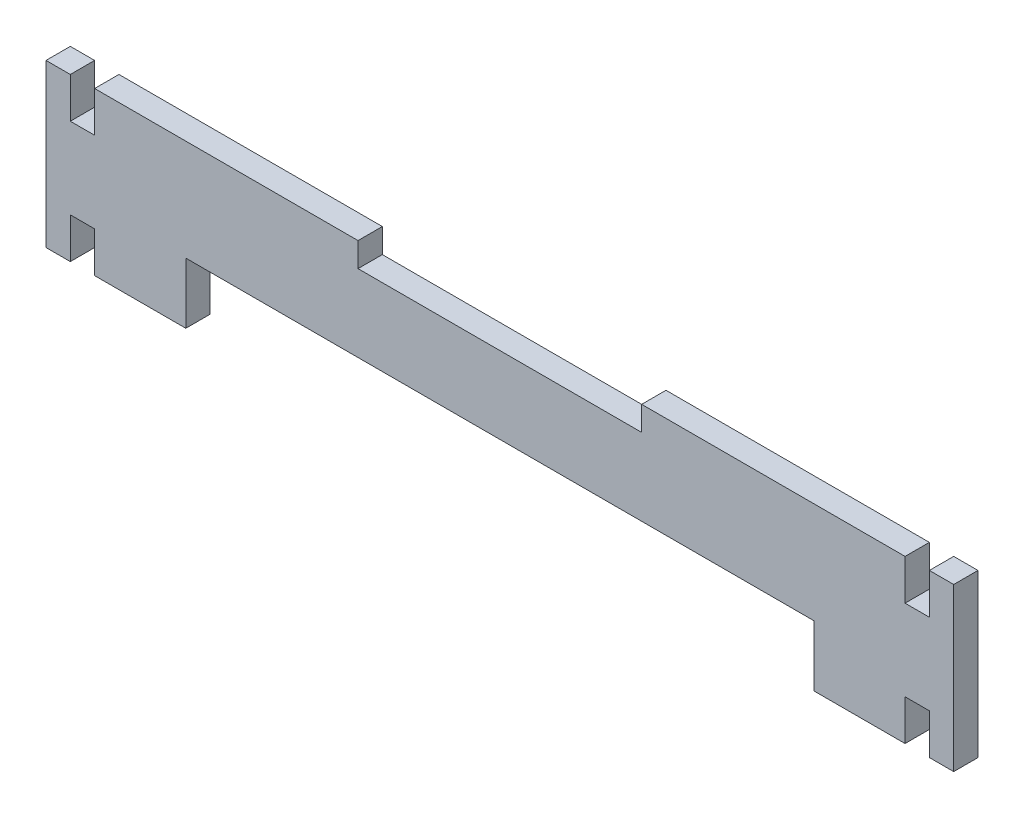
SolidWorks part; units mm, degrees
ref_plane "Front" through (0, 0, 0) normal (0, 0, 1) x (1, 0, 0)
ref_plane "Top" through (0, 0, 0) normal (0, 1, 0) x (1, 0, 0)
ref_plane "Right" through (0, 0, 0) normal (1, 0, 0) x (0, 0, -1)
sketch "Sketch1" plane through (0, 0, 0) normal (0, 0, 1) x (1, 0, 0)
  line L1 (0, 0) -> (-224, 0)
  line L2 (0, 0) -> (0, 40)
  line L3 (0, 40) -> (-224, 40)
  line L4 (-224, 0) -> (-224, 40)
  dimension "D1" = 40
  dimension "D2" = 224
extrude "Boss-Extrude1" add sketch "Sketch1" along normal blind 6
sketch "Sketch2" plane through (0, 0, 6) normal (0, 0, 1) x (1, 0, 0)
  line L0 (0, 40) -> (-224, 40) construction
  line L1 (-218, 40) -> (-212, 40)
  line L2 (-218, 40) -> (-218, 30)
  line L3 (-218, 30) -> (-212, 30)
  line L4 (-212, 40) -> (-212, 30)
  line L5 (-224, 40) -> (-224, 0) construction
  dimension "D1" = 10
  dimension "D2" = 6
  dimension "D3" = 6
extrude "Cut-Extrude1" cut sketch "Sketch2" against normal through all
pattern_linear "LPattern1" count 2 spacing 206 along (1, 0, 0) count 2 spacing 30 along (0, -1, 0) of "Cut-Extrude1"
sketch "Sketch3" plane through (0, 0, 6) normal (0, 0, 1) x (1, 0, 0)
  line L0 (-12, 40) -> (-212, 40) construction
  line L1 (-147, 40) -> (-77, 40)
  line L2 (-147, 40) -> (-147, 34)
  line L3 (-147, 34) -> (-77, 34)
  line L4 (-77, 40) -> (-77, 34)
  point P6 (-112, 40)
  point P7 (-112, 40)
  dimension "D1" = 70
  dimension "D2" = 6
extrude "Cut-Extrude2" cut sketch "Sketch3" against normal through all
sketch "Sketch4" plane through (0, 0, 6) normal (0, 0, 1) x (1, 0, 0)
  line L0 (-212, 0) -> (-12, 0) construction
  line L1 (-189.5, 0) -> (-34.5, 0)
  line L2 (-189.5, 0) -> (-189.5, 15)
  line L3 (-189.5, 15) -> (-34.5, 15)
  line L4 (-34.5, 0) -> (-34.5, 15)
  point P6 (-112, 0)
  point P7 (-112, 0)
  dimension "D1" = 15
  dimension "D2" = 155
extrude "Cut-Extrude3" cut sketch "Sketch4" against normal blind 10
